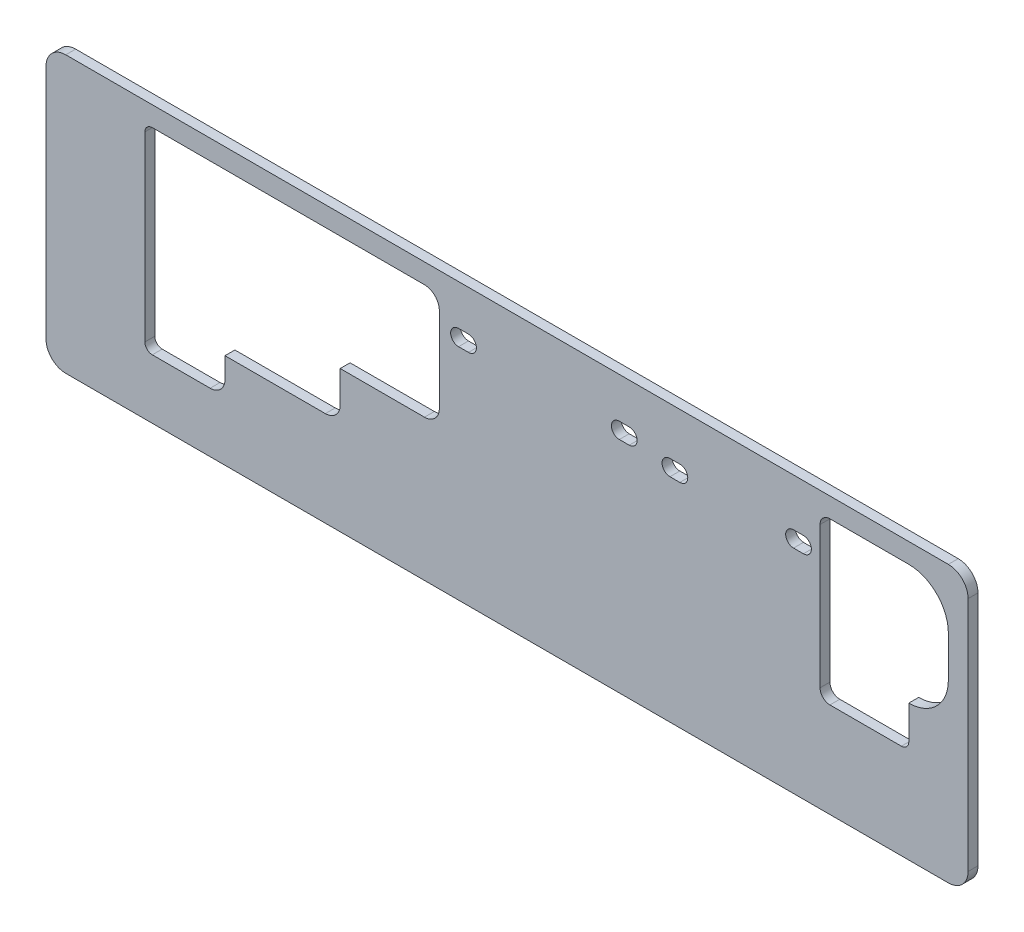
SolidWorks part; units mm, degrees
ref_plane "Front Plane" through (0, 0, 0) normal (0, 0, 1) x (1, 0, 0)
ref_plane "Top Plane" through (0, 0, 0) normal (0, 1, 0) x (1, 0, 0)
ref_plane "Right Plane" through (0, 0, 0) normal (1, 0, 0) x (0, 0, -1)
sketch "Sketch2" plane through (0, 0, 0) normal (0, 0, 1) x (1, 0, 0)
  line L0 (-742.8203, 0) -> (36398.195, 0) construction
  line L1 (76.25, 83.4381) -> (-76.25, 83.4381) construction
  line L2 (60.65, 30.6) -> (76.25, 30.6)
  line L3 (60.65, 30.6) -> (60.65, 0)
  line L4 (60.65, 0) -> (76.25, 0)
  line L5 (76.25, 30.6) -> (76.25, 0)
  line L6 (68.45, 0) -> (68.45, 30.6) construction
  line L7 (60.65, 15.3) -> (76.25, 15.3) construction
  line L8 (-35.65, 21.2) -> (-20.45, 21.2)
  line L9 (-35.65, 21.2) -> (-35.65, 0)
  line L10 (-35.65, 0) -> (-20.45, 0)
  line L11 (-20.45, 21.2) -> (-20.45, 0)
  line L12 (-28.05, 0) -> (-28.05, 21.2) construction
  line L13 (-35.65, 10.6) -> (-20.45, 10.6) construction
  line L14 (-14.95, 9.6) -> (21.85, 9.6)
  line L15 (-14.95, 9.6) -> (-14.95, 0)
  line L16 (-14.95, 0) -> (21.85, 0)
  line L17 (21.85, 9.6) -> (21.85, 0)
  line L18 (3.45, 0) -> (3.45, 9.6) construction
  line L19 (-14.95, 4.8) -> (21.85, 4.8) construction
  line L20 (57.95, 12.4) -> (26.95, 12.4)
  line L21 (57.95, 12.4) -> (57.95, 0)
  line L22 (57.95, 0) -> (26.95, 0)
  line L23 (26.95, 12.4) -> (26.95, 0)
  line L24 (42.45, 0) -> (42.45, 12.4) construction
  line L25 (57.95, 6.2) -> (26.95, 6.2) construction
  line L26 (-39.85, 30.6) -> (-58.25, 30.6)
  line L27 (-39.85, 30.6) -> (-39.85, 0)
  line L28 (-39.85, 0) -> (-58.25, 0)
  line L29 (-58.25, 30.6) -> (-58.25, 0)
  line L30 (-49.05, 0) -> (-49.05, 30.6) construction
  line L31 (-39.85, 15.3) -> (-58.25, 15.3) construction
  line L32 (-76.25, 37.8) -> (-63.85, 37.8)
  line L33 (-76.25, 37.8) -> (-76.25, 0)
  line L34 (-76.25, 0) -> (-63.85, 0)
  line L35 (-63.85, 37.8) -> (-63.85, 0)
  line L36 (-70.05, 0) -> (-70.05, 37.8) construction
  line L37 (-76.25, 18.9) -> (-63.85, 18.9) construction
  point P1 (68.45, 15.3)
  point P7 (-28.05, 10.6)
  point P11 (3.45, 4.8)
  point P15 (-49.05, 15.3)
  point P19 (42.45, 6.2)
  point P23 (-70.05, 18.9)
  point P29 (0, 83.4381)
  point P30 (-25.9772, 15.3)
  point P31 (5.4181, 4.8)
  point P32 (-19.0074, 10.6)
  point P33 (-43.0224, 30.6)
  dimension "D1" = 36.8
  dimension "D2" = 31
  dimension "D3" = 12.4
  dimension "D4" = 9.6
  dimension "D5" = 30.6
  dimension "D6" = 39
  dimension "D7" = 15.6
  dimension "D8" = 21.2
  dimension "D9" = 15.2
  dimension "D10" = 21
  dimension "D11" = 21
  dimension "D12" = 12.4
  dimension "D13" = 37.8
  dimension "D14" = 18.4
  dimension "D15" = 30.6
  dimension "D16" = 31.5
  dimension "D17" = 26
sketch "Sketch3" plane through (0, 0, 0) normal (0, 0, 1) x (1, 0, 0)
  line L16 (-77.25, -1) -> (-77.25, 38.8)
  line L17 (-77.25, 38.8) -> (-61.05, 38.8)
  line L18 (-61.05, 38.8) -> (-61.05, 31.6)
  line L20 (-61.05, 31.6) -> (-37.75, 31.6)
  line L22 (-37.75, 31.6) -> (-37.75, 22.2)
  line L23 (-37.75, 22.2) -> (-17.7, 22.2)
  line L24 (-17.7, 22.2) -> (-17.7, -1)
  line L26 (-17.7, -1) -> (-77.25, -1)
  line L27 (-70.05, 37.8) -> (-70.05, 38.8) construction
  line L28 (-76.25, 37.8) -> (-63.85, 37.8) construction
  line L30 (-58.25, 30.6) -> (-63.85, 30.6) construction
  line L33 (-63.85, 37.8) -> (-63.85, 0) construction
  line L38 (-49.05, 30.6) -> (-49.05, 31.6) construction
  line L39 (-35.65, 21.2) -> (-39.85, 21.2) construction
  line L40 (-39.85, 30.6) -> (-39.85, 0) construction
  line L41 (-14.95, 9.6) -> (-20.45, 9.6) construction
  line L42 (-20.45, 21.2) -> (-20.45, 0) construction
  line L43 (-200742.8203, 0) -> (236398.195, 0) construction
  line L44 (-28.05, 21.2) -> (-28.05, 22.2) construction
  line L45 (-76.25, 18.9) -> (-77.25, 18.9) construction
  line L46 (-76.25, 37.8) -> (-76.25, 0) construction
  line L47 (57.95, 6.2) -> (60.65, 6.2) construction
  line L48 (59.3, 31.6) -> (77.25, 31.6)
  line L49 (59.3, 31.6) -> (59.3, -1)
  line L50 (59.3, -1) -> (77.25, -1)
  line L51 (77.25, 31.6) -> (77.25, -1)
  line L52 (60.65, 30.6) -> (60.65, 0) construction
  line L53 (68.45, 0) -> (68.45, -1) construction
  line L54 (-28.05, 0) -> (-28.05, -1) construction
  line L55 (68.45, 30.6) -> (68.45, 31.6) construction
  line L56 (76.25, 15.3) -> (77.25, 15.3) construction
  line L58 (-97.25, 50.8) -> (89.25, 50.8)
  line L59 (-97.25, 50.8) -> (-97.25, -5)
  line L60 (-97.25, -5) -> (89.25, -5)
  line L61 (89.25, 50.8) -> (89.25, -5)
  point P31 (-17.7, 9.6)
  point P43 (-61.05, 30.6)
  point P44 (-37.75, 21.2)
  point P56 (59.3, 6.2)
  dimension "D1" = 1
  dimension "D2" = 1
  dimension "D3" = 1
  dimension "D4" = 4
  dimension "D5" = 12
  dimension "D6" = 20
  dimension "D7" = 12
extrude "Boss-Extrude1" add sketch "Sketch3" along normal blind 2
sketch "Sketch4" plane through (0, 0, 0) normal (0, 0, 1) x (1, 0, 0)
  line L0 (-13.805, 4.8) -> (-11.805, 4.8) construction
  line L1 (-13.805, 6.4) -> (-11.805, 6.4)
  line L2 (-13.805, 3.2) -> (-11.805, 3.2)
  line L3 (18.705, 4.8) -> (20.705, 4.8) construction
  line L4 (18.705, 6.4) -> (20.705, 6.4)
  line L5 (18.705, 3.2) -> (20.705, 3.2)
  line L6 (28.95, 6.2) -> (30.95, 6.2) construction
  line L7 (28.95, 7.8) -> (30.95, 7.8)
  line L8 (28.95, 4.6) -> (30.95, 4.6)
  line L9 (53.95, 6.2) -> (55.95, 6.2) construction
  line L10 (53.95, 7.8) -> (55.95, 7.8)
  line L11 (53.95, 4.6) -> (55.95, 4.6)
  line L12 (-12.805, 4.8) -> (19.705, 4.8) construction
  line L13 (29.95, 6.2) -> (54.95, 6.2) construction
  arc A0 (-13.805, 6.4) -> (-13.805, 3.2) centre (-13.805, 4.8) ccw
  arc A1 (-11.805, 3.2) -> (-11.805, 6.4) centre (-11.805, 4.8) ccw
  arc A2 (18.705, 6.4) -> (18.705, 3.2) centre (18.705, 4.8) ccw
  arc A3 (20.705, 3.2) -> (20.705, 6.4) centre (20.705, 4.8) ccw
  arc A4 (28.95, 7.8) -> (28.95, 4.6) centre (28.95, 6.2) ccw
  arc A5 (30.95, 4.6) -> (30.95, 7.8) centre (30.95, 6.2) ccw
  arc A6 (53.95, 7.8) -> (53.95, 4.6) centre (53.95, 6.2) ccw
  arc A7 (55.95, 4.6) -> (55.95, 7.8) centre (55.95, 6.2) ccw
  point P2 (-12.805, 4.8)
  point P8 (19.705, 4.8)
  point P15 (29.95, 6.2)
  point P22 (54.95, 6.2)
  point P30 (3.45, 4.8)
  point P34 (42.45, 6.2)
  dimension "D1" = 2
  dimension "D2" = 3.2
  dimension "D3" = 32.51
  dimension "D5" = 25
extrude "Cut-Extrude2" cut sketch "Sketch4" along normal through all
sketch "Sketch5" plane through (0, 0, 2) normal (0, 0, 1) x (1, 0, 0)
  line L5 (77.25, 15.3) -> (77.25, 7) construction
  line L6 (85.25, 15.3) -> (85.25, 7)
  line L7 (69.25, 15.3) -> (69.25, 7)
  line L8 (60.65, 15.3) -> (76.25, 15.3) construction
  line L9 (59.3, -1) -> (77.25, -1) construction
  line L10 (77.25, 31.6) -> (77.25, -1) construction
  arc A2 (85.25, 15.3) -> (69.25, 15.3) centre (77.25, 15.3) ccw
  arc A3 (69.25, 7) -> (85.25, 7) centre (77.25, 7) ccw
  point P2 (77.25, 11.15)
  point P10 (0, 0)
  point P13 (0, 0)
  point P16 (0, 0)
  dimension "D1" = 8
extrude "Cut-Extrude3" cut sketch "Sketch5" against normal through all
fillet "Fillet4" radius 4 4 edges at (89.25, -5, 1) (89.25, 50.8, 1) (-97.25, -5, 1) (-97.25, 50.8, 1)
fillet "Fillet5" radius 3 4 edges at (-17.7, -1, 1) (-17.7, 22.2, 1) (-37.75, 31.6, 1) (-61.05, 38.8, 1)
fillet "Fillet6" radius 1.5 3 edges at (77.25, 31.6, 1) (-77.25, 38.8, 1) (-77.25, -1, 1)
fillet "Fillet7" radius 2 2 edges at (59.3, -1, 1) (59.3, 31.6, 1)
mirror "Mirror1" about plane through (0, 0, 0) normal (0, 1, 0) of bodies 104
delete or keep bodies "Body-Delete/Keep 1" type delete bodies bodies 104
